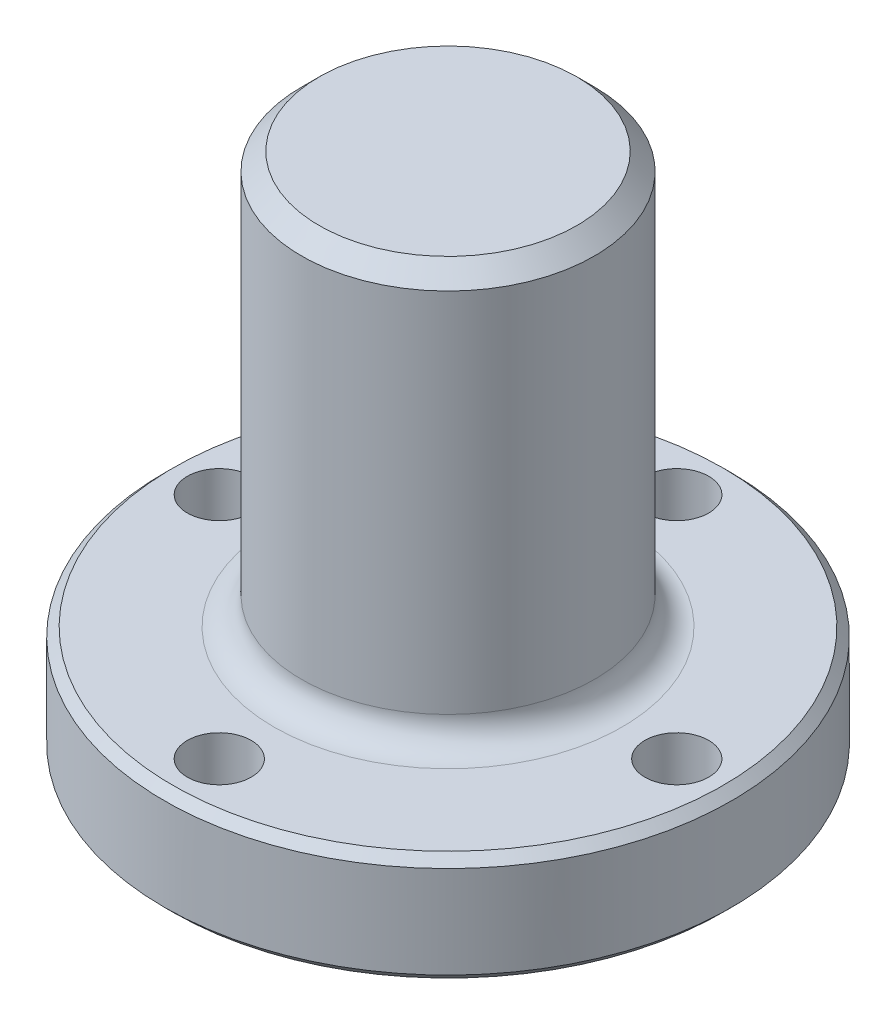
SolidWorks part; units mm, degrees
ref_plane "Front Plane" through (0, 0, 0) normal (1, 0, 0) x (0, 1, 0)
ref_plane "Top Plane" through (0, 0, 0) normal (0, 0, 1) x (0, 1, 0)
ref_plane "Right Plane" through (0, 0, 0) normal (0, 1, 0) x (-1, 0, 0)
sketch "Sketch1" plane through (0, 0, 0) normal (0, 0, 1) x (0, 1, 0)
  line L0 (-25.0317, 0) -> (-25.0317, 8.7122)
  line L1 (-25.0317, 8.7122) -> (-20.2057, 8.7122)
  line L2 (-20.2057, 8.7122) -> (-20.2057, 24.6126)
  line L3 (-20.2057, 24.6126) -> (-10.6807, 24.6126)
  line L4 (-10.6807, 24.6126) -> (-10.6807, 12.7)
  line L5 (-10.6807, 12.7) -> (25.0317, 12.7)
  line L6 (25.0317, 12.7) -> (25.0317, 0)
  line L7 (25.0317, 0) -> (-25.0317, 0)
  line L8 (-50.4317, 0) -> (50.4317, 0) construction
  point P10 (0, 0)
  dimension "D1" = 35.7124
  dimension "D2" = 45.2374
  dimension "D3" = 50.0634
  dimension "D4" = 11.9126
  dimension "D5" = 15.9004
  dimension "D6" = 24.6126
revolve "Revolve1" add sketch "Sketch1" angle 360 about L8
sketch "Sketch2" plane through (0, 0, 0) normal (0, 1, 0) x (-1, 0, 0)
  circle A0 centre (19.8374, 0) radius 2.7686
  circle A1 centre (0, 19.8374) radius 2.7686
  circle A2 centre (-19.8374, 0) radius 2.7686
  circle A3 centre (0, -19.8374) radius 2.7686
  point P8 (0, 0)
  dimension "D1" = 5.5372
  dimension "D2" = 5.5372
  dimension "D3" = 5.5372
  dimension "D4" = 5.5372
  dimension "D5" = 19.8374
  dimension "D6" = 39.6748
  dimension "D7" = 19.8374
  dimension "D8" = 39.6748
extrude "Cut-Extrude2" cut sketch "Sketch2" along normal blind 20.2057 from offset 20.2057
fillet "Fillet1" radius 2.3876 1 edges at (0, -10.6807, -12.7)
chamfer "Chamfer1" distance 0.762 angle 45 2 edges at (0, -10.6807, -24.6126) (0, -20.2057, -24.6126)
chamfer "Chamfer2" distance 1.524 angle 45 1 edges at (0, 25.0317, -12.7)
